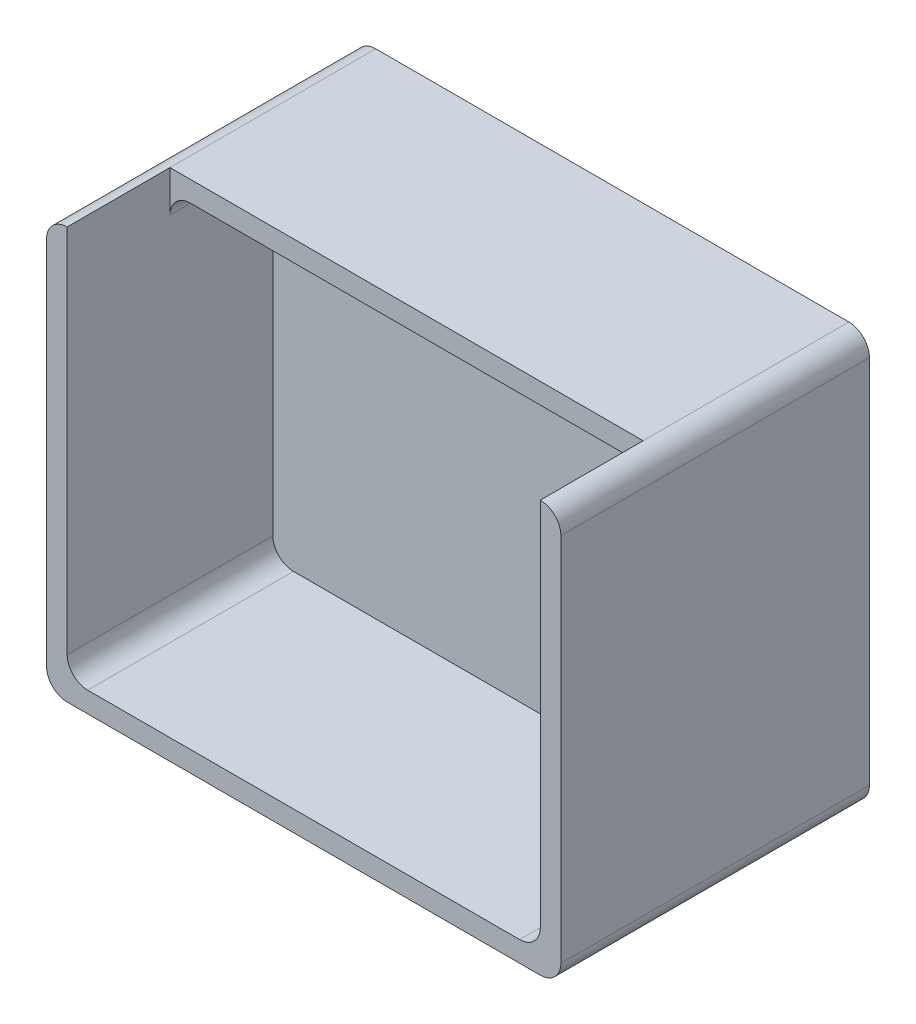
SolidWorks part; units mm, degrees
ref_plane "Plano frontal" through (0, 0, 0) normal (0, 0, 1) x (1, 0, 0)
ref_plane "Plano superior" through (0, 0, 0) normal (0, 1, 0) x (1, 0, 0)
ref_plane "Plano direito" through (0, 0, 0) normal (1, 0, 0) x (0, 0, -1)
sketch "Esboço1" plane through (0, 0, 0) normal (0, 0, 1) x (1, 0, 0)
  line L1 (12.5, -10) -> (-12.5, -10)
  line L2 (12.5, -10) -> (12.5, 10)
  line L3 (12.5, 10) -> (-12.5, 10)
  line L4 (-12.5, -10) -> (-12.5, 10)
  line L5 (12.5, -10) -> (-12.5, 10) construction
  line L6 (12.5, 10) -> (-12.5, -10) construction
  point P0 (0, 0)
extrude "Ressalto-extrusão1" add sketch "Esboço1" along normal blind 15
fillet "Filete1" radius 1 4 edges at (12.5, -10, 7.5) (12.5, 10, 7.5) (-12.5, -10, 7.5) (-12.5, 10, 7.5)
ref_plane "Plano1" through (0, 0, 15) normal (0, 0, 1) x (1, 0, 0)
sketch "Esboço2" plane through (0, 0, 15) normal (0, 0, 1) x (1, 0, 0)
  line L1 (11.5, -9) -> (-11.5, -9)
  line L2 (11.5, -9) -> (11.5, 9)
  line L3 (11.5, 9) -> (-11.5, 9)
  line L4 (-11.5, -9) -> (-11.5, 9)
  line L5 (11.5, -9) -> (-11.5, 9) construction
  line L6 (11.5, 9) -> (-11.5, -9) construction
  point P0 (0, 0)
extrude "Corte-extrusão1" cut sketch "Esboço2" against normal blind 10
fillet "Filete2" radius 1 4 edges at (11.5, 9, 10) (11.5, -9, 10) (-11.5, -9, 10) (-11.5, 9, 10)
sketch "Esboço6" plane through (0, 0, 0) normal (0, 0, 1) x (1, 0, 0)
  circle A0 centre (0, 0) radius 4
  circle A9 centre (7.3045, 5.2592) radius 4
  circle A10 centre (7.2845, -5.3108) radius 4
extrude "Corte-extrusão6" cut sketch "Esboço6" against normal blind 1 and the other way blind 2.5 contours A9 | A10 | A0
mirror "Espelhar1" about plane through (0, 0, 0) normal (1, 0, 0) of "Corte-extrusão6"
ref_plane "Plano2" through (0, 10, 0) normal (0, 1, 0) x (1, 0, 0)
sketch "Esboço7" plane through (0, 10, 0) normal (0, 1, 0) x (1, 0, 0)
  line L0 (11.5, -15) -> (11.5, 0) construction
  line L1 (-11.5, -15) -> (11.5, -15)
  line L2 (-11.5, -15) -> (-11.5, -10)
  line L3 (-11.5, -10) -> (11.5, -10)
  line L4 (11.5, -15) -> (11.5, -10)
extrude "Corte-extrusão7" cut sketch "Esboço7" against normal blind 2
